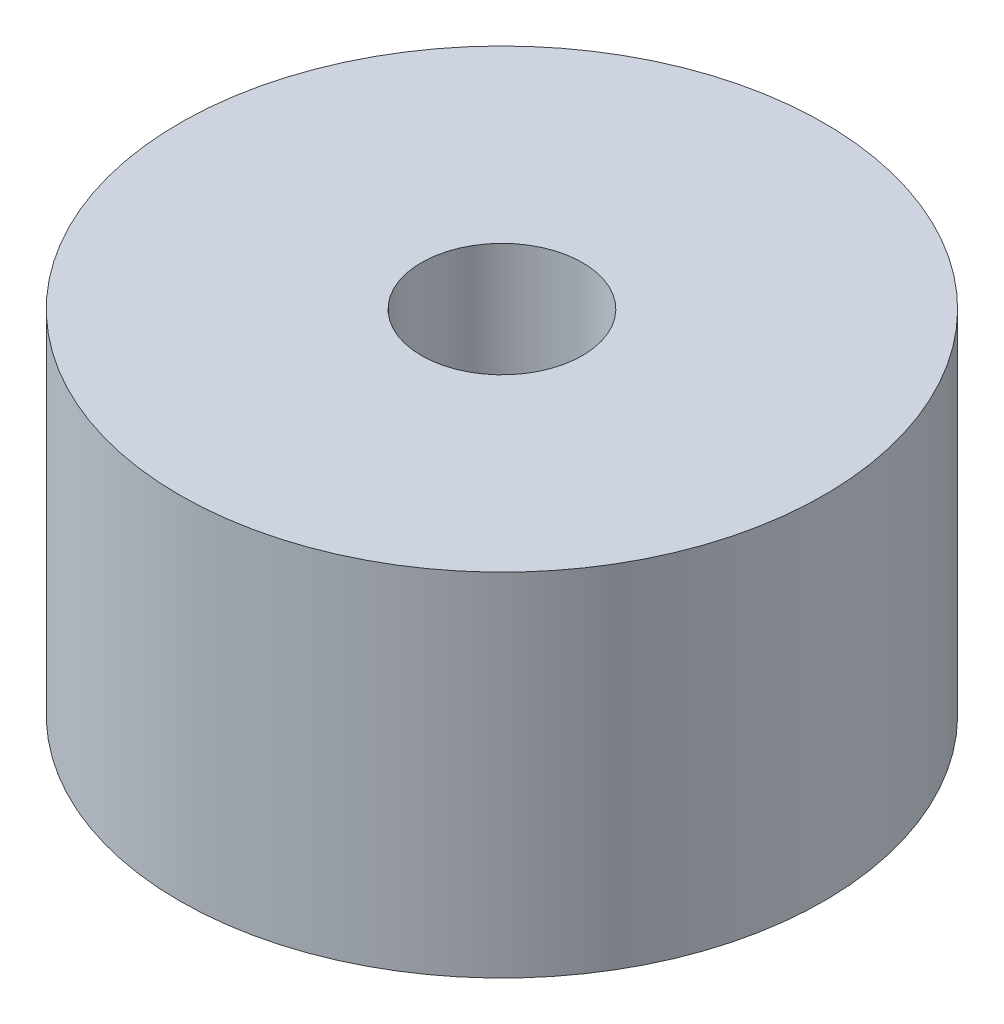
SolidWorks part; units mm, degrees
ref_plane "Front Plane" through (0, 0, 0) normal (0, 0, 1) x (1, 0, 0)
ref_plane "Top Plane" through (0, 0, 0) normal (0, 1, 0) x (1, 0, 0)
ref_plane "Right Plane" through (0, 0, 0) normal (1, 0, 0) x (0, 0, -1)
sketch "Sketch1" plane through (0, 0, 0) normal (0, 1, 0) x (1, 0, 0)
  circle A0 centre (0, 0) radius 1.375
  circle A1 centre (0, 0) radius 5.5
  dimension "D1" = 11
  dimension "D2" = 2.75
extrude "Boss-Extrude1" add sketch "Sketch1" along normal blind 6
